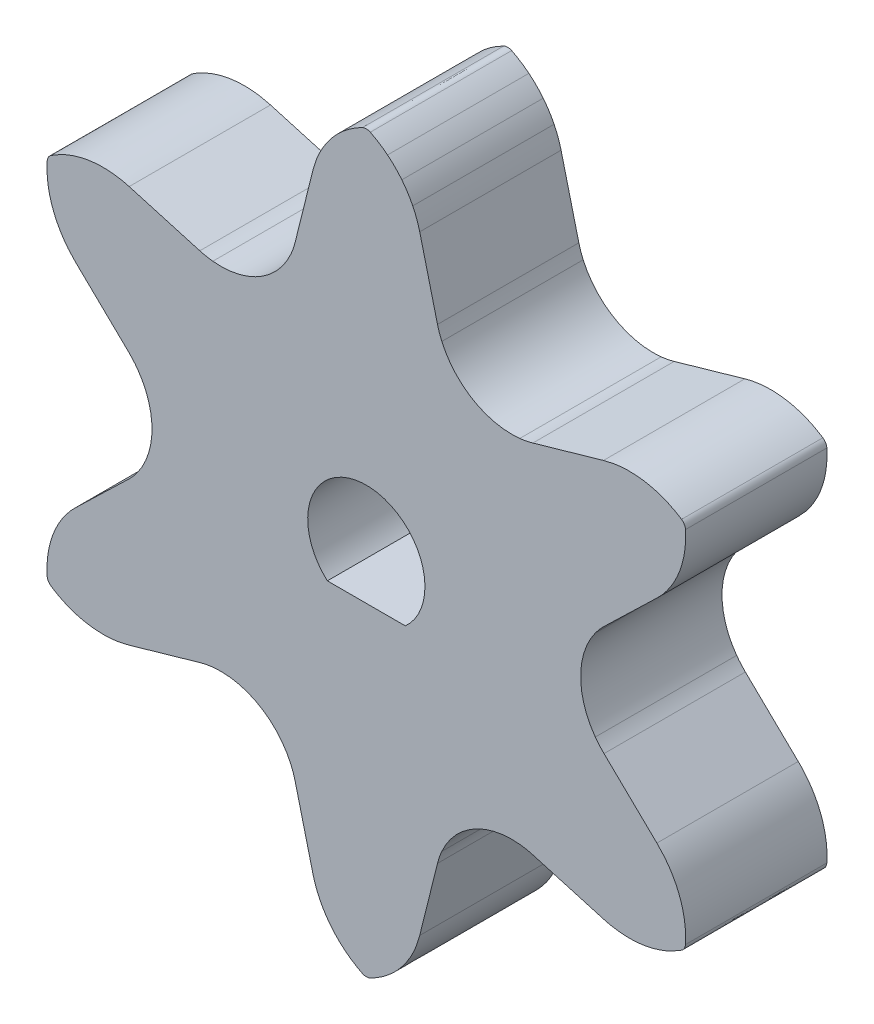
SolidWorks part; units mm, degrees
ref_plane "Front Plane" through (0, 0, 0) normal (0, 0, 1) x (1, 0, 0)
ref_plane "Top Plane" through (0, 0, 0) normal (0, 1, 0) x (1, 0, 0)
ref_plane "Right Plane" through (0, 0, 0) normal (1, 0, 0) x (0, 0, -1)
sketch "Sketch1" plane through (0, 0, 0) normal (0, 0, 1) x (1, 0, 0)
  point P0 (0, 0)
  line B0 (-1.3134, -1.475) -> (1.3134, -1.475)
  line B1 (1.7989, -10.2662) -> (2.3981, -7.8628)
  line B2 (-2.3981, -7.8628) -> (-1.7989, -10.2662)
  line B3 (9.7902, -3.5752) -> (8.0084, -1.8545)
  line B4 (5.6103, -6.0082) -> (7.9913, -6.691)
  line B5 (7.9913, 6.691) -> (5.6103, 6.0082)
  line B6 (8.0084, 1.8545) -> (9.7902, 3.5752)
  line B7 (-1.7989, 10.2662) -> (-2.3981, 7.8628)
  line B8 (2.3981, 7.8628) -> (1.7989, 10.2662)
  line B9 (-9.7902, 3.5752) -> (-8.0084, 1.8545)
  line B10 (-5.6103, 6.0082) -> (-7.9913, 6.691)
  line B11 (-7.9913, -6.691) -> (-5.6103, -6.0082)
  line B12 (-8.0084, -1.8545) -> (-9.7902, -3.5752)
  arc B13 (-2.5435, -7.44) -> (-5.1715, -5.9227) centre (-4.8997, -8.4865) ccw
  arc B14 (2.5435, -7.44) -> (2.3981, -7.8628) centre (4.8997, -8.4865) ccw
  arc B15 (0.1338, -12.34) -> (1.7989, -10.2662) centre (-1.2818, -9.4981) ccw
  arc B16 (-0.1338, -12.34) -> (0.1338, -12.34) centre (0, -12.0715) ccw
  arc B17 (-1.7989, -10.2662) -> (-0.1338, -12.34) centre (1.2818, -9.4981) ccw
  arc B18 (-2.3981, -7.8628) -> (-2.5435, -7.44) centre (-4.8997, -8.4865) ccw
  arc B19 (5.1715, -5.9227) -> (2.5435, -7.44) centre (4.8997, -8.4865) ccw
  arc B20 (7.715, -1.5173) -> (8.0084, -1.8545) centre (9.7993, 0) ccw
  arc B21 (10.7537, -6.0542) -> (9.7902, -3.5752) centre (7.5847, -5.8591) ccw
  arc B22 (10.6199, -6.2859) -> (10.7537, -6.0542) centre (10.4542, -6.0358) ccw
  arc B23 (7.9913, -6.691) -> (10.6199, -6.2859) centre (8.8664, -3.639) ccw
  arc B24 (5.6103, -6.0082) -> (5.1715, -5.9227) centre (4.8997, -8.4865) ccw
  arc B25 (7.715, 1.5173) -> (7.715, -1.5173) centre (9.7993, 0) ccw
  arc B26 (5.1715, 5.9227) -> (5.6103, 6.0082) centre (4.8997, 8.4865) ccw
  arc B27 (10.6199, 6.2859) -> (7.9913, 6.691) centre (8.8664, 3.639) ccw
  arc B28 (10.7537, 6.0542) -> (10.6199, 6.2859) centre (10.4542, 6.0358) ccw
  arc B29 (9.7902, 3.5752) -> (10.7537, 6.0542) centre (7.5847, 5.8591) ccw
  arc B30 (8.0084, 1.8545) -> (7.715, 1.5173) centre (9.7993, 0) ccw
  arc B31 (2.5435, 7.44) -> (5.1715, 5.9227) centre (4.8997, 8.4865) ccw
  arc B32 (-2.5435, 7.44) -> (-2.3981, 7.8628) centre (-4.8997, 8.4865) ccw
  arc B33 (-0.1338, 12.34) -> (-1.7989, 10.2662) centre (1.2818, 9.4981) ccw
  arc B34 (0.1338, 12.34) -> (-0.1338, 12.34) centre (0, 12.0715) ccw
  arc B35 (1.7989, 10.2662) -> (0.1338, 12.34) centre (-1.2818, 9.4981) ccw
  arc B36 (2.3981, 7.8628) -> (2.5435, 7.44) centre (4.8997, 8.4865) ccw
  arc B37 (-5.1715, 5.9227) -> (-2.5435, 7.44) centre (-4.8997, 8.4865) ccw
  arc B38 (-7.715, -1.5173) -> (-7.715, 1.5173) centre (-9.7993, 0) ccw
  arc B39 (-7.715, 1.5173) -> (-8.0084, 1.8545) centre (-9.7993, 0) ccw
  arc B40 (-10.7537, 6.0542) -> (-9.7902, 3.5752) centre (-7.5847, 5.8591) ccw
  arc B41 (-10.6199, 6.2859) -> (-10.7537, 6.0542) centre (-10.4542, 6.0358) ccw
  arc B42 (-7.9913, 6.691) -> (-10.6199, 6.2859) centre (-8.8664, 3.639) ccw
  arc B43 (-5.6103, 6.0082) -> (-5.1715, 5.9227) centre (-4.8997, 8.4865) ccw
  arc B44 (-5.1715, -5.9227) -> (-5.6103, -6.0082) centre (-4.8997, -8.4865) ccw
  arc B45 (-10.6199, -6.2859) -> (-7.9913, -6.691) centre (-8.8664, -3.639) ccw
  arc B46 (-10.7537, -6.0542) -> (-10.6199, -6.2859) centre (-10.4542, -6.0358) ccw
  arc B47 (-9.7902, -3.5752) -> (-10.7537, -6.0542) centre (-7.5847, -5.8591) ccw
  arc B48 (-8.0084, -1.8545) -> (-7.715, -1.5173) centre (-9.7993, 0) ccw
  arc B49 (1.3134, -1.475) -> (-1.3134, -1.475) centre (0, 0) ccw
  arc B50 (7.715, 1.5173) -> (7.715, -1.5173) centre (9.7993, 0) ccw
  arc B51 (2.5435, 7.44) -> (5.1715, 5.9227) centre (4.8997, 8.4865) ccw
  arc B52 (-2.5435, -7.44) -> (-5.1715, -5.9227) centre (-4.8997, -8.4865) ccw
  arc B53 (-5.1715, 5.9227) -> (-2.5435, 7.44) centre (-4.8997, 8.4865) ccw
  arc B54 (5.1715, -5.9227) -> (2.5435, -7.44) centre (4.8997, -8.4865) ccw
  arc B55 (-7.715, -1.5173) -> (-7.715, 1.5173) centre (-9.7993, 0) ccw
  spline B56 degree 3 poles (8.0084, -1.8545) (7.901, -1.7508) (7.8031, -1.6384) (7.715, -1.5173) knots 0 0 0 0 1 1 1 1
  spline B57 degree 3 poles (9.7902, -3.5752) (9.1967, -3.002) (8.6029, -2.4286) (8.0084, -1.8545) knots 0 0 0 0 1 1 1 1
  spline B58 degree 3 poles (10.7537, -6.0542) (10.7679, -5.8229) (10.7568, -5.5947) (10.6865, -5.1439) (10.6259, -4.9191) (10.4604, -4.4943) (10.3558, -4.2926) (10.1023, -3.9112) (9.9552, -3.7345) (9.7902, -3.5752) knots 0 0 0 0 0.25 0.25 0.5 0.5 0.75 0.75 1 1 1 1
  spline B59 degree 3 poles (10.7537, -6.0542) (10.7479, -6.147) (10.6975, -6.2345) (10.6199, -6.2859) knots 0 0 0 0 1 1 1 1
  spline B60 degree 3 poles (7.9913, -6.691) (8.2118, -6.7542) (8.4354, -6.7927) (8.8883, -6.822) (9.1203, -6.812) (9.5709, -6.7432) (9.791, -6.6851) (10.2204, -6.52) (10.4267, -6.4138) (10.6199, -6.2859) knots 0 0 0 0 0.25 0.25 0.5 0.5 0.75 0.75 1 1 1 1
  spline B61 degree 3 poles (7.9913, -6.691) (7.1982, -6.4635) (6.4046, -6.236) (5.6103, -6.0082) knots 0 0 0 0 1 1 1 1
  spline B62 degree 3 poles (5.1715, -5.9227) (5.3205, -5.9385) (5.4667, -5.9671) (5.6103, -6.0082) knots 0 0 0 0 1 1 1 1
  spline B63 degree 3 poles (-2.3981, 7.8628) (-2.4343, 7.7178) (-2.4827, 7.5769) (-2.5435, 7.44) knots 0 0 0 0 1 1 1 1
  spline B64 degree 3 poles (-1.7989, 10.2662) (-1.9985, 9.4656) (-2.1982, 8.6646) (-2.3981, 7.8628) knots 0 0 0 0 1 1 1 1
  spline B65 degree 3 poles (-0.1338, 12.34) (-0.3411, 12.2367) (-0.5333, 12.113) (-0.8885, 11.8267) (-1.0529, 11.6618) (-1.338, 11.3061) (-1.4604, 11.1147) (-1.664, 10.7045) (-1.7434, 10.4887) (-1.7989, 10.2662) knots 0 0 0 0 0.25 0.25 0.5 0.5 0.75 0.75 1 1 1 1
  spline B66 degree 3 poles (-0.1338, 12.34) (-0.0505, 12.3815) (0.0505, 12.3815) (0.1338, 12.34) knots 0 0 0 0 1 1 1 1
  spline B67 degree 3 poles (1.7989, 10.2662) (1.7434, 10.4887) (1.665, 10.7016) (1.4639, 11.1085) (1.3392, 11.3044) (1.0543, 11.6603) (0.8939, 11.8218) (0.5363, 12.1111) (0.3412, 12.2367) (0.1338, 12.34) knots 0 0 0 0 0.25 0.25 0.5 0.5 0.75 0.75 1 1 1 1
  spline B68 degree 3 poles (1.7989, 10.2662) (1.9985, 9.4656) (2.1982, 8.6646) (2.3981, 7.8628) knots 0 0 0 0 1 1 1 1
  spline B69 degree 3 poles (2.5435, 7.44) (2.4827, 7.5769) (2.4343, 7.7178) (2.3981, 7.8628) knots 0 0 0 0 1 1 1 1
  spline B70 degree 3 poles (2.3981, -7.8628) (2.4343, -7.7178) (2.4827, -7.5769) (2.5435, -7.44) knots 0 0 0 0 1 1 1 1
  spline B71 degree 3 poles (1.7989, -10.2662) (1.9985, -9.4656) (2.1982, -8.6646) (2.3981, -7.8628) knots 0 0 0 0 1 1 1 1
  spline B72 degree 3 poles (0.1338, -12.34) (0.3411, -12.2367) (0.5333, -12.113) (0.8885, -11.8267) (1.0529, -11.6618) (1.338, -11.3061) (1.4604, -11.1147) (1.664, -10.7045) (1.7434, -10.4887) (1.7989, -10.2662) knots 0 0 0 0 0.25 0.25 0.5 0.5 0.75 0.75 1 1 1 1
  spline B73 degree 3 poles (0.1338, -12.34) (0.0505, -12.3815) (-0.0505, -12.3815) (-0.1338, -12.34) knots 0 0 0 0 1 1 1 1
  spline B74 degree 3 poles (-1.7989, -10.2662) (-1.7434, -10.4887) (-1.665, -10.7016) (-1.4639, -11.1085) (-1.3392, -11.3044) (-1.0543, -11.6603) (-0.8939, -11.8218) (-0.5363, -12.1111) (-0.3412, -12.2367) (-0.1338, -12.34) knots 0 0 0 0 0.25 0.25 0.5 0.5 0.75 0.75 1 1 1 1
  spline B75 degree 3 poles (-1.7989, -10.2662) (-1.9985, -9.4656) (-2.1982, -8.6646) (-2.3981, -7.8628) knots 0 0 0 0 1 1 1 1
  spline B76 degree 3 poles (-2.5435, -7.44) (-2.4827, -7.5769) (-2.4343, -7.7178) (-2.3981, -7.8628) knots 0 0 0 0 1 1 1 1
  spline B77 degree 3 poles (-8.0084, 1.8545) (-7.901, 1.7508) (-7.8031, 1.6384) (-7.715, 1.5173) knots 0 0 0 0 1 1 1 1
  spline B78 degree 3 poles (-9.7902, 3.5752) (-9.1967, 3.002) (-8.6029, 2.4286) (-8.0084, 1.8545) knots 0 0 0 0 1 1 1 1
  spline B79 degree 3 poles (-10.7537, 6.0542) (-10.7679, 5.8229) (-10.7568, 5.5947) (-10.6865, 5.1439) (-10.6259, 4.9191) (-10.4604, 4.4943) (-10.3558, 4.2926) (-10.1023, 3.9112) (-9.9552, 3.7345) (-9.7902, 3.5752) knots 0 0 0 0 0.25 0.25 0.5 0.5 0.75 0.75 1 1 1 1
  spline B80 degree 3 poles (-10.7537, 6.0542) (-10.7479, 6.147) (-10.6975, 6.2345) (-10.6199, 6.2859) knots 0 0 0 0 1 1 1 1
  spline B81 degree 3 poles (-7.9913, 6.691) (-8.2118, 6.7542) (-8.4354, 6.7927) (-8.8883, 6.822) (-9.1203, 6.812) (-9.5709, 6.7432) (-9.791, 6.6851) (-10.2204, 6.52) (-10.4267, 6.4138) (-10.6199, 6.2859) knots 0 0 0 0 0.25 0.25 0.5 0.5 0.75 0.75 1 1 1 1
  spline B82 degree 3 poles (-7.9913, 6.691) (-7.1982, 6.4635) (-6.4046, 6.236) (-5.6103, 6.0082) knots 0 0 0 0 1 1 1 1
  spline B83 degree 3 poles (-5.1715, 5.9227) (-5.3205, 5.9385) (-5.4667, 5.9671) (-5.6103, 6.0082) knots 0 0 0 0 1 1 1 1
  spline B84 degree 3 poles (5.6103, 6.0082) (5.4667, 5.9671) (5.3205, 5.9385) (5.1715, 5.9227) knots 0 0 0 0 1 1 1 1
  spline B85 degree 3 poles (7.9913, 6.691) (7.1982, 6.4635) (6.4046, 6.236) (5.6103, 6.0082) knots 0 0 0 0 1 1 1 1
  spline B86 degree 3 poles (10.6199, 6.2859) (10.4268, 6.4138) (10.2235, 6.5184) (9.798, 6.6828) (9.573, 6.7427) (9.1224, 6.8118) (8.8955, 6.8221) (8.4383, 6.7933) (8.2118, 6.7542) (7.9913, 6.691) knots 0 0 0 0 0.25 0.25 0.5 0.5 0.75 0.75 1 1 1 1
  spline B87 degree 3 poles (10.6199, 6.2859) (10.6975, 6.2345) (10.7479, 6.147) (10.7537, 6.0542) knots 0 0 0 0 1 1 1 1
  spline B88 degree 3 poles (9.7902, 3.5752) (9.9552, 3.7345) (10.1004, 3.9089) (10.3522, 4.2865) (10.4595, 4.4924) (10.6253, 4.9171) (10.6849, 5.1368) (10.7567, 5.5911) (10.7679, 5.8229) (10.7537, 6.0542) knots 0 0 0 0 0.25 0.25 0.5 0.5 0.75 0.75 1 1 1 1
  spline B89 degree 3 poles (8.0084, 1.8545) (8.6029, 2.4286) (9.1967, 3.002) (9.7902, 3.5752) knots 0 0 0 0 1 1 1 1
  spline B90 degree 3 poles (7.715, 1.5173) (7.8031, 1.6384) (7.901, 1.7508) (8.0084, 1.8545) knots 0 0 0 0 1 1 1 1
  spline B91 degree 3 poles (-7.9913, -6.691) (-7.1982, -6.4635) (-6.4046, -6.236) (-5.6103, -6.0082) knots 0 0 0 0 1 1 1 1
  spline B92 degree 3 poles (-10.6199, -6.2859) (-10.4268, -6.4138) (-10.2235, -6.5184) (-9.798, -6.6828) (-9.573, -6.7427) (-9.1224, -6.8118) (-8.8955, -6.8221) (-8.4383, -6.7933) (-8.2118, -6.7542) (-7.9913, -6.691) knots 0 0 0 0 0.25 0.25 0.5 0.5 0.75 0.75 1 1 1 1
  spline B93 degree 3 poles (-10.6199, -6.2859) (-10.6975, -6.2345) (-10.7479, -6.147) (-10.7537, -6.0542) knots 0 0 0 0 1 1 1 1
  spline B94 degree 3 poles (-9.7902, -3.5752) (-9.9552, -3.7345) (-10.1004, -3.9089) (-10.3522, -4.2865) (-10.4595, -4.4924) (-10.6253, -4.9171) (-10.6849, -5.1368) (-10.7567, -5.5911) (-10.7679, -5.8229) (-10.7537, -6.0542) knots 0 0 0 0 0.25 0.25 0.5 0.5 0.75 0.75 1 1 1 1
  spline B95 degree 3 poles (-8.0084, -1.8545) (-8.6029, -2.4286) (-9.1967, -3.002) (-9.7902, -3.5752) knots 0 0 0 0 1 1 1 1
  spline B96 degree 3 poles (-5.6103, -6.0082) (-5.4667, -5.9671) (-5.3205, -5.9385) (-5.1715, -5.9227) knots 0 0 0 0 1 1 1 1
  spline B97 degree 3 poles (-7.715, -1.5173) (-7.8031, -1.6384) (-7.901, -1.7508) (-8.0084, -1.8545) knots 0 0 0 0 1 1 1 1
sketch_block_instance "motorsprocket-1"
sketch_block "motorsprocket"
other "DetailItem3"
other "DetailItem4"
extrude "Boss-Extrude1" add sketch "Sketch1" along normal blind 4.7625 contours B38 B97 B12 B47 B93 B45 B11 B96 B13 B76 B2 B17 B74 B73 B15 B1 B70 B19 B62 B4 B23 B59 B21 B3 B56 B25 B90 B6 B29 B87 B27 B5 B84 B31 B69 B8 B35 B67 B66 B33 B7 B63 B37 B83 B10 B42 B80
